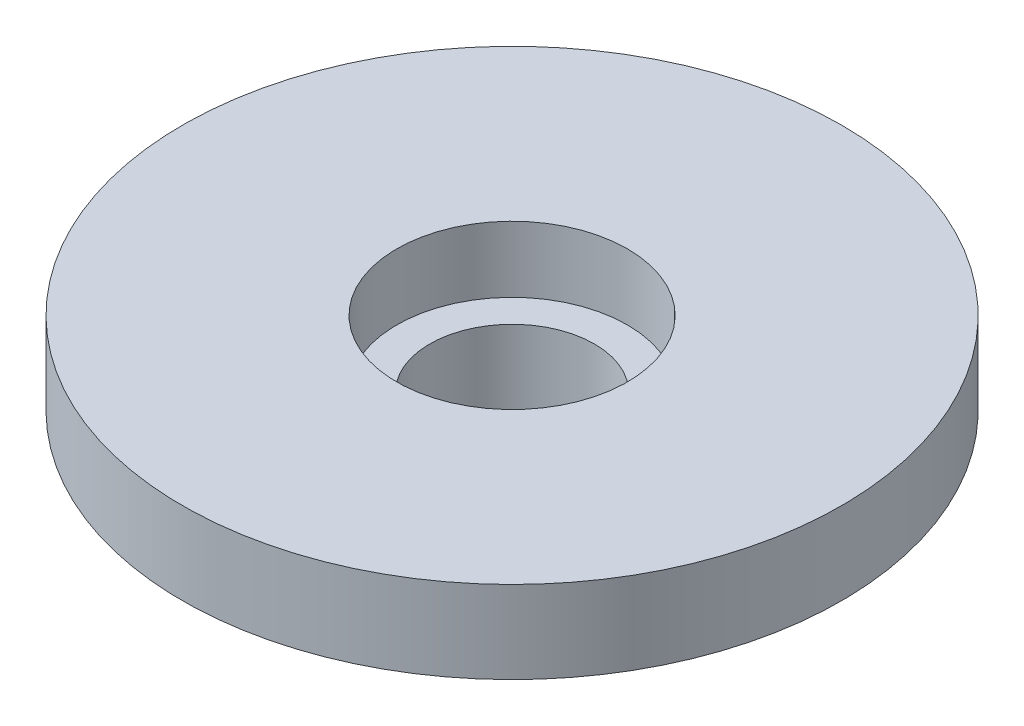
SolidWorks part; units mm, degrees
ref_plane "Front Plane" through (0, 0, 0) normal (0, 0, 1) x (1, 0, 0)
ref_plane "Top Plane" through (0, 0, 0) normal (0, 1, 0) x (1, 0, 0)
ref_plane "Right Plane" through (0, 0, 0) normal (1, 0, 0) x (0, 0, -1)
sketch "Sketch1" plane through (0, 0, 0) normal (0, 0, 1) x (1, 0, 0)
  line L0 (0, 0) -> (0, 19.3754) construction
  line L2 (2.5, 2.5) -> (3.5, 2.5)
  line L3 (3.5, 2.5) -> (3.5, 4.5)
  line L4 (3.5, 4.5) -> (10, 4.5)
  line L5 (10, 4.5) -> (10, 2)
  line L6 (10, 2) -> (5, 2)
  line L7 (5, 2) -> (5, 0)
  line L8 (5, 0) -> (2.5, 0)
  line L9 (2.5, 2.5) -> (2.5, 0)
  dimension "D1" = 20
  dimension "D2" = 7
  dimension "D3" = 10
  dimension "D4" = 5
  dimension "D5" = 2.5
  dimension "D6" = 4.5
  dimension "D7" = 2
revolve "Revolve1" add sketch "Sketch1" angle 360 about L0
